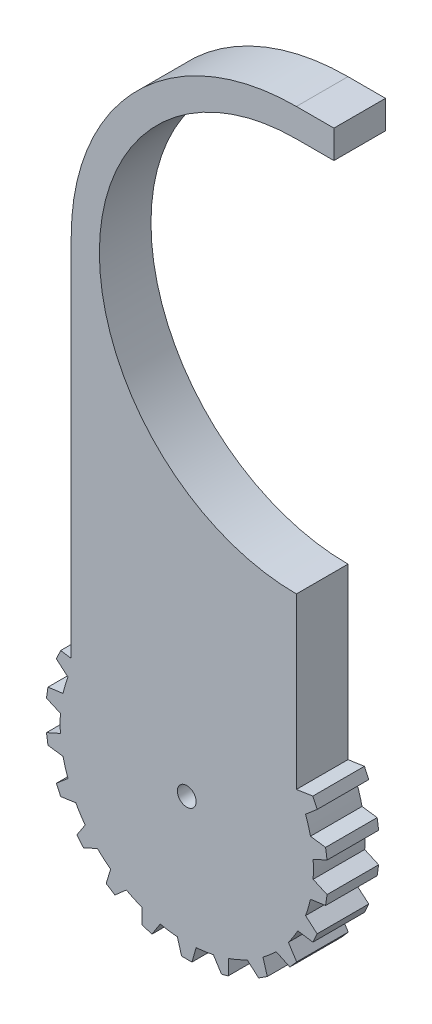
SolidWorks part; units mm, degrees
ref_plane "Front Plane" through (0, 0, 0) normal (0, 0, 1) x (1, 0, 0)
ref_plane "Top Plane" through (0, 0, 0) normal (0, 1, 0) x (1, 0, 0)
ref_plane "Right Plane" through (0, 0, 0) normal (1, 0, 0) x (0, 0, -1)
sketch "Sketch1" plane through (0, 0, 0) normal (0, 0, 1) x (1, 0, 0)
  line L0 (0, 21) -> (0, 24)
  line L2 (-24, 0) -> (-24, -38.9517)
  line L8 (0, -21) -> (0, -39.0465)
  line L9 (-16.4486, -59.7897) -> (-16.4378, -58.1627)
  line L10 (-15.3893, -60.1008) -> (-14.5188, -58.7262)
  line L11 (-20.274, -57.87) -> (-19.3452, -58.4669)
  line L12 (-20.274, -57.87) -> (-19.8052, -56.312)
  line L13 (-19.3452, -58.4669) -> (-18.1227, -57.3932)
  line L37 (-7.2628, -59.899) -> (-7.9864, -60.0929)
  line L39 (-7.2628, -59.899) -> (-7.235, -58.2722)
  line L40 (-11.1333, -60.554) -> (-12.2374, -60.554)
  line L41 (-12.2374, -60.554) -> (-12.6854, -58.9898)
  line L42 (-11.1333, -60.554) -> (-10.6854, -58.9898)
  line L67 (-22.6806, -55.7847) -> (-23.4036, -54.9503)
  line L68 (-23.4036, -54.9503) -> (-22.5148, -53.5875)
  line L69 (-22.6806, -55.7847) -> (-21.2051, -55.099)
  line L70 (-25.1251, -52.2715) -> (-25.5838, -51.2672)
  line L71 (-25.5838, -51.2672) -> (-24.3471, -50.21)
  line L72 (-25.1251, -52.2715) -> (-23.5162, -52.0292)
  line L73 (-26.4809, -48.2119) -> (-26.638, -47.119)
  line L74 (-26.638, -47.119) -> (-25.1535, -46.453)
  line L75 (-26.4809, -48.2119) -> (-24.8689, -48.4327)
  line L76 (-26.638, -43.9347) -> (-26.4809, -42.8419)
  line L77 (-26.4809, -42.8419) -> (-24.8689, -42.6211)
  line L78 (-26.638, -43.9347) -> (-25.1535, -44.6007)
  line L79 (-25.5838, -39.7866) -> (-25.1251, -38.7823)
  line L80 (-25.1251, -38.7823) -> (-24, -38.9517)
  line L81 (-25.5838, -39.7866) -> (-24.3471, -40.8438)
  line L103 (1.7544, -38.7823) -> (2.2131, -39.7866)
  line L104 (2.2131, -39.7866) -> (0.9764, -40.8438)
  line L105 (1.7544, -38.7823) -> (0, -39.0465)
  line L106 (3.1102, -42.8419) -> (3.2673, -43.9347)
  line L107 (3.2673, -43.9347) -> (1.7828, -44.6007)
  line L108 (3.1102, -42.8419) -> (1.4982, -42.6211)
  line L109 (3.2673, -47.119) -> (3.1102, -48.2119)
  line L110 (3.1102, -48.2119) -> (1.4982, -48.4327)
  line L111 (3.2673, -47.119) -> (1.7828, -46.453)
  line L112 (2.2131, -51.2672) -> (1.7544, -52.2715)
  line L113 (1.7544, -52.2715) -> (0.1455, -52.0292)
  line L114 (2.2131, -51.2672) -> (0.9764, -50.21)
  line L115 (0.0329, -54.9503) -> (-0.6902, -55.7847)
  line L116 (-0.6902, -55.7847) -> (-2.1656, -55.099)
  line L117 (0.0329, -54.9503) -> (-0.8559, -53.5875)
  line L118 (-3.0967, -57.87) -> (-4.0255, -58.4669)
  line L119 (-4.0255, -58.4669) -> (-5.248, -57.3932)
  line L120 (-3.0967, -57.87) -> (-3.5655, -56.312)
  line L121 (-7.2627, -59.8897) -> (-7.9814, -60.1008)
  line L122 (-7.9814, -60.1008) -> (-8.8519, -58.7262)
  line L123 (-16.4486, -59.7897) -> (-15.3893, -60.1008)
  line L148 (-15.3893, -60.1008) -> (-15.7474, -59.9956) [skipped]
  line L149 (-6.9221, -59.7897) -> (-6.9329, -58.1627) [skipped]
  line L150 (-23.4036, -36.1034) -> (-22.6806, -35.269) [skipped]
  line L151 (-23.4036, -36.1034) -> (-22.5148, -37.4663) [skipped]
  line L152 (-22.6806, -35.269) -> (-21.2051, -35.9548) [skipped]
  line L153 (-20.274, -33.1838) -> (-19.8052, -34.7418) [skipped]
  line L154 (-19.3452, -32.5869) -> (-18.1227, -33.6605) [skipped]
  line L155 (-20.274, -33.1838) -> (-19.3452, -32.5869) [skipped]
  line L156 (-16.4486, -31.264) -> (-16.4378, -32.891) [skipped]
  line L157 (-15.3893, -30.953) -> (-14.5188, -32.3276) [skipped]
  line L158 (-16.4486, -31.264) -> (-15.3893, -30.953) [skipped]
  line L159 (-12.2374, -30.4998) -> (-12.6854, -32.064) [skipped]
  line L160 (-12.2374, -30.4998) -> (-11.1333, -30.4998) [skipped]
  line L161 (-11.1333, -30.4998) -> (-10.6854, -32.064) [skipped]
  line L162 (-7.9814, -30.953) -> (-8.8519, -32.3276) [skipped]
  line L163 (-6.9221, -31.264) -> (-6.9329, -32.891) [skipped]
  line L164 (-7.9814, -30.953) -> (-6.9221, -31.264) [skipped]
  line L165 (-4.0255, -32.5869) -> (-5.248, -33.6605) [skipped]
  line L166 (-3.0967, -33.1838) -> (-3.5655, -34.7418) [skipped]
  line L167 (-4.0255, -32.5869) -> (-3.0967, -33.1838) [skipped]
  line L168 (-0.6902, -35.269) -> (-2.1656, -35.9548) [skipped]
  line L169 (0, -36.0655) -> (0.0329, -36.1034) [skipped]
  line L170 (0.0329, -36.1034) -> (0, -36.1538) [skipped]
  line L171 (-19.5087, -58.3619) -> (-19.6746, -58.2552) [skipped]
  arc A0 (0, 21) -> (0, -21) centre (0, 0) ccw
  arc A1 (0, 24) -> (-24, 0) centre (0, 0) ccw
  arc A58 (-24.3471, -40.8438) -> (-24.8689, -42.6211) centre (-11.6854, -45.5269) ccw
  arc A59 (-25.1535, -44.6007) -> (-25.1535, -46.453) centre (-11.6854, -45.5269) ccw
  arc A60 (-24.8689, -48.4327) -> (-24.3471, -50.21) centre (-11.6854, -45.5269) ccw
  arc A61 (-21.2051, -55.099) -> (-19.8052, -56.312) centre (-11.6854, -45.5269) ccw
  arc A62 (-23.5162, -52.0292) -> (-22.5148, -53.5875) centre (-11.6854, -45.5269) ccw
  arc A63 (-18.1227, -57.3932) -> (-16.4378, -58.1627) centre (-11.6854, -45.5269) ccw
  arc A64 (-14.5188, -58.7262) -> (-12.6854, -58.9898) centre (-11.6854, -45.5269) ccw
  arc A65 (-10.6854, -58.9898) -> (-8.8519, -58.7262) centre (-11.6854, -45.5269) ccw
  arc A66 (-7.235, -58.2722) -> (-5.248, -57.3932) centre (-11.6854, -45.5269) ccw
  arc A67 (-3.5655, -56.312) -> (-2.1656, -55.099) centre (-11.6854, -45.5269) ccw
  arc A68 (-0.8559, -53.5875) -> (0.1455, -52.0292) centre (-11.6854, -45.5269) ccw
  arc A69 (0.9764, -50.21) -> (1.4982, -48.4327) centre (-11.6854, -45.5269) ccw
  arc A70 (1.7828, -46.453) -> (1.7828, -44.6007) centre (-11.6854, -45.5269) ccw
  arc A71 (1.4982, -42.6211) -> (0.9764, -40.8438) centre (-11.6854, -45.5269) ccw
  point P100 (-11.6854, -45.5269)
  point P109 (-11.6854, -45.5269)
  point P110 (-11.002, -45.4371)
  point P164 (-11.6854, -45.5269)
  dimension "D1" = 42
  dimension "D5" = 22
  dimension "D2" = 3
extrude "Boss-Extrude1" add sketch "Sketch1" along normal blind 3 contours L108 A71 L104 L103 L105 L8 A0 L0 A1 L2 L80 L79 L81 A58 L77 L76 L78 A59 L74 L73 L75 A60 L71 L70 L72 A62 L68 L67 L69 A61 L12 L11 L13 A63 L9 L123 L10 A64 L41 L40 L42 A65 L122 L37 L121 L39 A66 L119 L118 L120 A67
sketch "Sketch3" plane through (0, 0, 0) normal (1, 0, 0) x (0, 0, -1)
  line L4 (0, 21) -> (0, 24)
  line L5 (0, 24) -> (-3, 24)
  line L6 (-3, 24) -> (-3, 21)
  line L7 (-3, 21) -> (0, 21)
  line L8 (0, 21) -> (0, 24)
  line L9 (0, 24) -> (-3, 24)
  line L10 (-3, 24) -> (-3, 21)
  line L11 (-3, 21) -> (0, 21)
  dimension "D1" = 0
extrude "Boss-Extrude2" add sketch "Sketch3" along normal blind 4
sketch "Sketch4" plane through (0, 0, 0) normal (0, 0, -1) x (-1, 0, 0)
  line L51 (-1.4982, -42.6211) -> (-3.1102, -42.8419)
  line L52 (-3.1102, -42.8419) -> (-3.2673, -43.9347)
  line L53 (-3.2673, -43.9347) -> (-1.7828, -44.6007)
  line L54 (-1.7828, -46.453) -> (-3.2673, -47.119)
  line L55 (-3.2673, -47.119) -> (-3.1102, -48.2119)
  line L56 (-3.1102, -48.2119) -> (-1.4982, -48.4327)
  line L57 (-0.9764, -50.21) -> (-2.2131, -51.2672)
  line L58 (-2.2131, -51.2672) -> (-1.7544, -52.2715)
  line L59 (-1.7544, -52.2715) -> (-0.1455, -52.0292)
  line L60 (0.8559, -53.5875) -> (-0.0329, -54.9503)
  line L61 (-0.0329, -54.9503) -> (0.6902, -55.7847)
  line L62 (0.6902, -55.7847) -> (2.1656, -55.099)
  line L63 (3.5655, -56.312) -> (3.0967, -57.87)
  line L64 (3.0967, -57.87) -> (4.0255, -58.4669)
  line L65 (4.0255, -58.4669) -> (5.248, -57.3932)
  line L66 (7.235, -58.2722) -> (7.2627, -59.8897)
  line L67 (7.2627, -59.8897) -> (7.6233, -59.9956)
  line L68 (7.6233, -59.9956) -> (7.9864, -60.0929)
  line L69 (7.9864, -60.0929) -> (8.8519, -58.7262)
  line L70 (10.6854, -58.9898) -> (11.1333, -60.554)
  line L71 (11.1333, -60.554) -> (12.2374, -60.554)
  line L72 (12.2374, -60.554) -> (12.6854, -58.9898)
  line L73 (14.5188, -58.7262) -> (15.3893, -60.1008)
  line L74 (15.3893, -60.1008) -> (16.4486, -59.7897)
  line L75 (16.4486, -59.7897) -> (16.4378, -58.1627)
  line L76 (18.1227, -57.3932) -> (19.3452, -58.4669)
  line L77 (19.3452, -58.4669) -> (20.274, -57.87)
  line L78 (20.274, -57.87) -> (19.8052, -56.312)
  line L79 (21.2051, -55.099) -> (22.6806, -55.7847)
  line L80 (22.6806, -55.7847) -> (23.4036, -54.9503)
  line L81 (23.4036, -54.9503) -> (22.5148, -53.5875)
  line L82 (23.5162, -52.0292) -> (25.1251, -52.2715)
  line L83 (25.1251, -52.2715) -> (25.5838, -51.2672)
  line L84 (25.5838, -51.2672) -> (24.3471, -50.21)
  line L85 (24.8689, -48.4327) -> (26.4809, -48.2119)
  line L86 (26.4809, -48.2119) -> (26.638, -47.119)
  line L87 (26.638, -47.119) -> (25.1535, -46.453)
  line L88 (25.1535, -44.6007) -> (26.638, -43.9347)
  line L89 (26.638, -43.9347) -> (26.4809, -42.8419)
  line L90 (26.4809, -42.8419) -> (24.8689, -42.6211)
  line L91 (24.3471, -40.8438) -> (25.5838, -39.7866)
  line L92 (25.5838, -39.7866) -> (25.1251, -38.7823)
  line L93 (25.1251, -38.7823) -> (24, -38.9517)
  line L94 (24, -38.9517) -> (24, 0)
  line L95 (0, 24) -> (-4, 24)
  line L96 (-4, 24) -> (-4, 21)
  line L97 (-4, 21) -> (0, 21)
  line L98 (0, -21) -> (0, -39.0465)
  line L99 (0, -39.0465) -> (-1.7544, -38.7823)
  line L100 (-1.7544, -38.7823) -> (-2.2131, -39.7866)
  line L101 (-2.2131, -39.7866) -> (-0.9764, -40.8438)
  line L102 (-1.4982, -42.6211) -> (-3.1102, -42.8419)
  line L103 (-3.1102, -42.8419) -> (-3.2673, -43.9347)
  line L104 (-3.2673, -43.9347) -> (-1.7828, -44.6007)
  line L105 (-1.7828, -46.453) -> (-3.2673, -47.119)
  line L106 (-3.2673, -47.119) -> (-3.1102, -48.2119)
  line L107 (-3.1102, -48.2119) -> (-1.4982, -48.4327)
  line L108 (-0.9764, -50.21) -> (-2.2131, -51.2672)
  line L109 (-2.2131, -51.2672) -> (-1.7544, -52.2715)
  line L110 (-1.7544, -52.2715) -> (-0.1455, -52.0292)
  line L111 (0.8559, -53.5875) -> (-0.0329, -54.9503)
  line L112 (-0.0329, -54.9503) -> (0.6902, -55.7847)
  line L113 (0.6902, -55.7847) -> (2.1656, -55.099)
  line L114 (3.5655, -56.312) -> (3.0967, -57.87)
  line L115 (3.0967, -57.87) -> (4.0255, -58.4669)
  line L116 (4.0255, -58.4669) -> (5.248, -57.3932)
  line L117 (7.235, -58.2722) -> (7.2627, -59.8897)
  line L118 (7.2627, -59.8897) -> (7.6233, -59.9956)
  line L119 (7.6233, -59.9956) -> (7.9864, -60.0929)
  line L120 (7.9864, -60.0929) -> (8.8519, -58.7262)
  line L121 (10.6854, -58.9898) -> (11.1333, -60.554)
  line L122 (11.1333, -60.554) -> (12.2374, -60.554)
  line L123 (12.2374, -60.554) -> (12.6854, -58.9898)
  line L124 (14.5188, -58.7262) -> (15.3893, -60.1008)
  line L125 (15.3893, -60.1008) -> (16.4486, -59.7897)
  line L126 (16.4486, -59.7897) -> (16.4378, -58.1627)
  line L127 (18.1227, -57.3932) -> (19.3452, -58.4669)
  line L128 (19.3452, -58.4669) -> (20.274, -57.87)
  line L129 (20.274, -57.87) -> (19.8052, -56.312)
  line L130 (21.2051, -55.099) -> (22.6806, -55.7847)
  line L131 (22.6806, -55.7847) -> (23.4036, -54.9503)
  line L132 (23.4036, -54.9503) -> (22.5148, -53.5875)
  line L133 (23.5162, -52.0292) -> (25.1251, -52.2715)
  line L134 (25.1251, -52.2715) -> (25.5838, -51.2672)
  line L135 (25.5838, -51.2672) -> (24.3471, -50.21)
  line L136 (24.8689, -48.4327) -> (26.4809, -48.2119)
  line L137 (26.4809, -48.2119) -> (26.638, -47.119)
  line L138 (26.638, -47.119) -> (25.1535, -46.453)
  line L139 (25.1535, -44.6007) -> (26.638, -43.9347)
  line L140 (26.638, -43.9347) -> (26.4809, -42.8419)
  line L141 (26.4809, -42.8419) -> (24.8689, -42.6211)
  line L142 (24.3471, -40.8438) -> (25.5838, -39.7866)
  line L143 (25.5838, -39.7866) -> (25.1251, -38.7823)
  line L144 (25.1251, -38.7823) -> (24, -38.9517)
  line L145 (24, -38.9517) -> (24, 0)
  line L146 (0, 24) -> (-4, 24)
  line L147 (-4, 24) -> (-4, 21)
  line L148 (-4, 21) -> (0, 21)
  line L149 (0, -21) -> (0, -39.0465)
  line L150 (0, -39.0465) -> (-1.7544, -38.7823)
  line L151 (-1.7544, -38.7823) -> (-2.2131, -39.7866)
  line L152 (-2.2131, -39.7866) -> (-0.9764, -40.8438)
  arc A16 (-1.7828, -44.6007) -> (-1.7828, -46.453) centre (11.6854, -45.5269) ccw
  arc A17 (-1.4982, -48.4327) -> (-0.9764, -50.21) centre (11.6854, -45.5269) ccw
  arc A18 (-0.1455, -52.0292) -> (0.8559, -53.5875) centre (11.6854, -45.5269) ccw
  arc A19 (2.1656, -55.099) -> (3.5655, -56.312) centre (11.6854, -45.5269) ccw
  arc A20 (5.248, -57.3932) -> (7.235, -58.2722) centre (11.6854, -45.5269) ccw
  arc A21 (8.8519, -58.7262) -> (10.6854, -58.9898) centre (11.6854, -45.5269) ccw
  arc A22 (12.6854, -58.9898) -> (14.5188, -58.7262) centre (11.6854, -45.5269) ccw
  arc A23 (16.4378, -58.1627) -> (18.1227, -57.3932) centre (11.6854, -45.5269) ccw
  arc A24 (19.8052, -56.312) -> (21.2051, -55.099) centre (11.6854, -45.5269) ccw
  arc A25 (22.5148, -53.5875) -> (23.5162, -52.0292) centre (11.6854, -45.5269) ccw
  arc A26 (24.3471, -50.21) -> (24.8689, -48.4327) centre (11.6854, -45.5269) ccw
  arc A27 (25.1535, -46.453) -> (25.1535, -44.6007) centre (11.6854, -45.5269) ccw
  arc A28 (24.8689, -42.6211) -> (24.3471, -40.8438) centre (11.6854, -45.5269) ccw
  arc A29 (24, 0) -> (0, 24) centre (0, 0) ccw
  arc A30 (0, -21) -> (0, 21) centre (0, 0) ccw
  arc A31 (-0.9764, -40.8438) -> (-1.4982, -42.6211) centre (11.6854, -45.5269) ccw
  arc A32 (-1.7828, -44.6007) -> (-1.7828, -46.453) centre (11.6854, -45.5269) ccw
  arc A33 (-1.4982, -48.4327) -> (-0.9764, -50.21) centre (11.6854, -45.5269) ccw
  arc A34 (-0.1455, -52.0292) -> (0.8559, -53.5875) centre (11.6854, -45.5269) ccw
  arc A35 (2.1656, -55.099) -> (3.5655, -56.312) centre (11.6854, -45.5269) ccw
  arc A36 (5.248, -57.3932) -> (7.235, -58.2722) centre (11.6854, -45.5269) ccw
  arc A37 (8.8519, -58.7262) -> (10.6854, -58.9898) centre (11.6854, -45.5269) ccw
  arc A38 (12.6854, -58.9898) -> (14.5188, -58.7262) centre (11.6854, -45.5269) ccw
  arc A39 (16.4378, -58.1627) -> (18.1227, -57.3932) centre (11.6854, -45.5269) ccw
  arc A40 (19.8052, -56.312) -> (21.2051, -55.099) centre (11.6854, -45.5269) ccw
  arc A41 (22.5148, -53.5875) -> (23.5162, -52.0292) centre (11.6854, -45.5269) ccw
  arc A42 (24.3471, -50.21) -> (24.8689, -48.4327) centre (11.6854, -45.5269) ccw
  arc A43 (25.1535, -46.453) -> (25.1535, -44.6007) centre (11.6854, -45.5269) ccw
  arc A44 (24.8689, -42.6211) -> (24.3471, -40.8438) centre (11.6854, -45.5269) ccw
  arc A45 (24, 0) -> (0, 24) centre (0, 0) ccw
  arc A46 (0, -21) -> (0, 21) centre (0, 0) ccw
  arc A47 (-0.9764, -40.8438) -> (-1.4982, -42.6211) centre (11.6854, -45.5269) ccw
  dimension "D1" = 0
extrude "Boss-Extrude3" add sketch "Sketch4" along normal blind 2.5
sketch "Sketch5" plane through (0, 0, 3) normal (0, 0, 1) x (1, 0, 0)
  circle A0 centre (-11.6854, -45.5269) radius 1
  dimension "D1" = 2
extrude "Cut-Extrude1" cut sketch "Sketch5" against normal up to next
